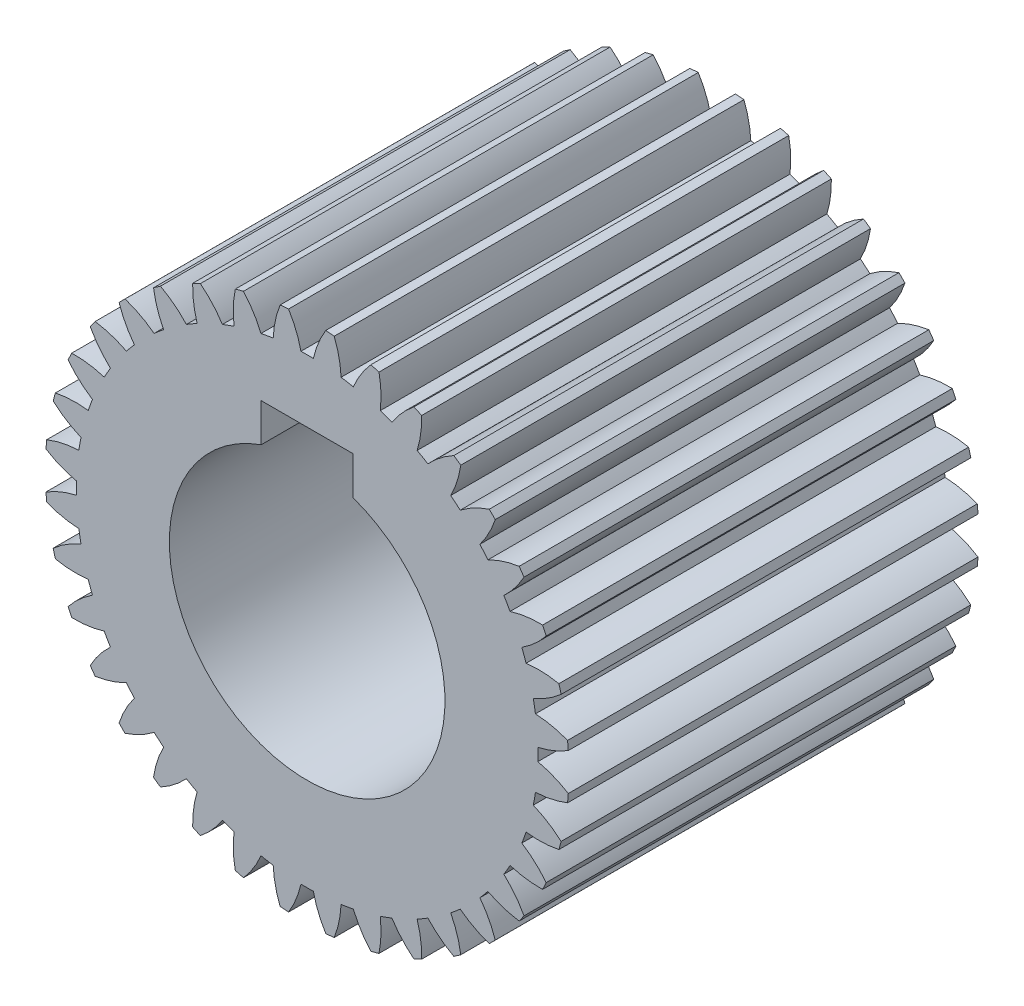
SolidWorks part; units mm, degrees
ref_plane "前视基准面" through (0, 0, 0) normal (0, 0, 1) x (1, 0, 0)
ref_plane "上视基准面" through (0, 0, 0) normal (0, 1, 0) x (1, 0, 0)
ref_plane "右视基准面" through (0, 0, 0) normal (1, 0, 0) x (0, 0, -1)
sketch "Model" plane through (0, 0, 0) normal (0, 0, 1) x (1, 0, 0)
  line L0 (-5, 18.3) -> (-5, 14.1421)
  line L1 (5, 18.3) -> (-5, 18.3)
  line L2 (5, 14.1421) -> (5, 18.3)
  arc A0 (25.1149, 0.6756) -> (28.4281, 2.0233) centre (22.7583, 11.2153) ccw
  arc A1 (28.4281, 2.0233) -> (28.3475, 2.9439) centre (0, 0) ccw
  arc A2 (28.3475, 2.9439) -> (24.8507, 3.6958) centre (24.3601, -7.093) ccw
  arc A3 (24.8507, 3.6958) -> (24.616, 5.0265) centre (0, 0) ccw
  arc A4 (24.616, 5.0265) -> (27.6449, 6.9291) centre (20.465, 14.9969) ccw
  arc A5 (27.6449, 6.9291) -> (27.4057, 7.8217) centre (0, 0) ccw
  arc A6 (27.4057, 7.8217) -> (23.8314, 7.955) centre (25.2217, -2.7552) ccw
  arc A7 (23.8314, 7.955) -> (23.3692, 9.2247) centre (0, 0) ccw
  arc A8 (23.3692, 9.2247) -> (26.0216, 11.6243) centre (17.5499, 18.3228) ccw
  arc A9 (26.0216, 11.6243) -> (25.6311, 12.4618) centre (0, 0) ccw
  arc A10 (25.6311, 12.4618) -> (22.088, 11.9724) centre (25.3169, 1.6664) ccw
  arc A11 (22.088, 11.9724) -> (21.4124, 13.1425) centre (0, 0) ccw
  arc A12 (21.4124, 13.1425) -> (23.6078, 15.9663) centre (14.1016, 21.0919) ccw
  arc A13 (23.6078, 15.9663) -> (23.0777, 16.7233) centre (0, 0) ccw
  arc A14 (23.0777, 16.7233) -> (19.6734, 15.626) centre (24.6429, 6.0373) ccw
  arc A15 (19.6734, 15.626) -> (18.8049, 16.6611) centre (0, 0) ccw
  arc A16 (18.8049, 16.6611) -> (20.4766, 19.8232) centre (10.2248, 23.2202) ccw
  arc A17 (20.4766, 19.8232) -> (19.8232, 20.4766) centre (0, 0) ccw
  arc A18 (19.8232, 20.4766) -> (16.6611, 18.8049) centre (23.2202, 10.2248) ccw
  arc A19 (16.6611, 18.8049) -> (15.626, 19.6734) centre (0, 0) ccw
  arc A20 (15.626, 19.6734) -> (16.7233, 23.0777) centre (6.0373, 24.6429) ccw
  arc A21 (16.7233, 23.0777) -> (15.9663, 23.6078) centre (0, 0) ccw
  arc A22 (15.9663, 23.6078) -> (13.1425, 21.4124) centre (21.0919, 14.1016) ccw
  arc A23 (13.1425, 21.4124) -> (11.9724, 22.088) centre (0, 0) ccw
  arc A24 (11.9724, 22.088) -> (12.4618, 25.6311) centre (1.6664, 25.3169) ccw
  arc A25 (12.4618, 25.6311) -> (11.6243, 26.0216) centre (0, 0) ccw
  arc A26 (11.6243, 26.0216) -> (9.2247, 23.3692) centre (18.3228, 17.5499) ccw
  arc A27 (9.2247, 23.3692) -> (7.955, 23.8314) centre (0, 0) ccw
  arc A28 (7.955, 23.8314) -> (7.8217, 27.4057) centre (-2.7552, 25.2217) ccw
  arc A29 (7.8217, 27.4057) -> (6.9291, 27.6449) centre (0, 0) ccw
  arc A30 (6.9291, 27.6449) -> (5.0265, 24.616) centre (14.9969, 20.465) ccw
  arc A31 (5.0265, 24.616) -> (3.6958, 24.8507) centre (0, 0) ccw
  arc A32 (3.6958, 24.8507) -> (2.9439, 28.3475) centre (-7.093, 24.3601) ccw
  arc A33 (2.9439, 28.3475) -> (2.0233, 28.4281) centre (0, 0) ccw
  arc A34 (2.0233, 28.4281) -> (0.6756, 25.1149) centre (11.2153, 22.7583) ccw
  arc A35 (0.6756, 25.1149) -> (-0.6756, 25.1149) centre (0, 0) ccw
  arc A36 (-0.6756, 25.1149) -> (-2.0233, 28.4281) centre (-11.2153, 22.7583) ccw
  arc A37 (-2.0233, 28.4281) -> (-2.9439, 28.3475) centre (0, 0) ccw
  arc A38 (-2.9439, 28.3475) -> (-3.6958, 24.8507) centre (7.093, 24.3601) ccw
  arc A39 (-3.6958, 24.8507) -> (-5.0265, 24.616) centre (0, 0) ccw
  arc A40 (-5.0265, 24.616) -> (-6.9291, 27.6449) centre (-14.9969, 20.465) ccw
  arc A41 (-6.9291, 27.6449) -> (-7.8217, 27.4057) centre (0, 0) ccw
  arc A42 (-7.8217, 27.4057) -> (-7.955, 23.8314) centre (2.7552, 25.2217) ccw
  arc A43 (-7.955, 23.8314) -> (-9.2247, 23.3692) centre (0, 0) ccw
  arc A44 (-9.2247, 23.3692) -> (-11.6243, 26.0216) centre (-18.3228, 17.5499) ccw
  arc A45 (-11.6243, 26.0216) -> (-12.4618, 25.6311) centre (0, 0) ccw
  arc A46 (-12.4618, 25.6311) -> (-11.9724, 22.088) centre (-1.6664, 25.3169) ccw
  arc A47 (-11.9724, 22.088) -> (-13.1425, 21.4124) centre (0, 0) ccw
  arc A48 (-13.1425, 21.4124) -> (-15.9663, 23.6078) centre (-21.0919, 14.1016) ccw
  arc A49 (-15.9663, 23.6078) -> (-16.7233, 23.0777) centre (0, 0) ccw
  arc A50 (-16.7233, 23.0777) -> (-15.626, 19.6734) centre (-6.0373, 24.6429) ccw
  arc A51 (-15.626, 19.6734) -> (-16.6611, 18.8049) centre (0, 0) ccw
  arc A52 (-16.6611, 18.8049) -> (-19.8232, 20.4766) centre (-23.2202, 10.2248) ccw
  arc A53 (-19.8232, 20.4766) -> (-20.4766, 19.8232) centre (0, 0) ccw
  arc A54 (-20.4766, 19.8232) -> (-18.8049, 16.6611) centre (-10.2248, 23.2202) ccw
  arc A55 (-18.8049, 16.6611) -> (-19.6734, 15.626) centre (0, 0) ccw
  arc A56 (-19.6734, 15.626) -> (-23.0777, 16.7233) centre (-24.6429, 6.0373) ccw
  arc A57 (-23.0777, 16.7233) -> (-23.6078, 15.9663) centre (0, 0) ccw
  arc A58 (-23.6078, 15.9663) -> (-21.4124, 13.1425) centre (-14.1016, 21.0919) ccw
  arc A59 (-21.4124, 13.1425) -> (-22.088, 11.9724) centre (0, 0) ccw
  arc A60 (-22.088, 11.9724) -> (-25.6311, 12.4618) centre (-25.3169, 1.6664) ccw
  arc A61 (-25.6311, 12.4618) -> (-26.0216, 11.6243) centre (0, 0) ccw
  arc A62 (-26.0216, 11.6243) -> (-23.3692, 9.2247) centre (-17.5499, 18.3228) ccw
  arc A63 (-23.3692, 9.2247) -> (-23.8314, 7.955) centre (0, 0) ccw
  arc A64 (-23.8314, 7.955) -> (-27.4057, 7.8217) centre (-25.2217, -2.7552) ccw
  arc A65 (-27.4057, 7.8217) -> (-27.6449, 6.9291) centre (0, 0) ccw
  arc A66 (-27.6449, 6.9291) -> (-24.616, 5.0265) centre (-20.465, 14.9969) ccw
  arc A67 (-24.616, 5.0265) -> (-24.8507, 3.6958) centre (0, 0) ccw
  arc A68 (-24.8507, 3.6958) -> (-28.3475, 2.9439) centre (-24.3601, -7.093) ccw
  arc A69 (-28.3475, 2.9439) -> (-28.4281, 2.0233) centre (0, 0) ccw
  arc A70 (-28.4281, 2.0233) -> (-25.1149, 0.6756) centre (-22.7583, 11.2153) ccw
  arc A71 (-25.1149, 0.6756) -> (-25.1149, -0.6756) centre (0, 0) ccw
  arc A72 (-25.1149, -0.6756) -> (-28.4281, -2.0233) centre (-22.7583, -11.2153) ccw
  arc A73 (-28.4281, -2.0233) -> (-28.3475, -2.9439) centre (0, 0) ccw
  arc A74 (-28.3475, -2.9439) -> (-24.8507, -3.6958) centre (-24.3601, 7.093) ccw
  arc A75 (-24.8507, -3.6958) -> (-24.616, -5.0265) centre (0, 0) ccw
  arc A76 (-24.616, -5.0265) -> (-27.6449, -6.9291) centre (-20.465, -14.9969) ccw
  arc A77 (-27.6449, -6.9291) -> (-27.4057, -7.8217) centre (0, 0) ccw
  arc A78 (-27.4057, -7.8217) -> (-23.8314, -7.955) centre (-25.2217, 2.7552) ccw
  arc A79 (-23.8314, -7.955) -> (-23.3692, -9.2247) centre (0, 0) ccw
  arc A80 (-23.3692, -9.2247) -> (-26.0216, -11.6243) centre (-17.5499, -18.3228) ccw
  arc A81 (-26.0216, -11.6243) -> (-25.6311, -12.4618) centre (0, 0) ccw
  arc A82 (-25.6311, -12.4618) -> (-22.088, -11.9724) centre (-25.3169, -1.6664) ccw
  arc A83 (-22.088, -11.9724) -> (-21.4124, -13.1425) centre (0, 0) ccw
  arc A84 (-21.4124, -13.1425) -> (-23.6078, -15.9663) centre (-14.1016, -21.0919) ccw
  arc A85 (-23.6078, -15.9663) -> (-23.0777, -16.7233) centre (0, 0) ccw
  arc A86 (-23.0777, -16.7233) -> (-19.6734, -15.626) centre (-24.6429, -6.0373) ccw
  arc A87 (-19.6734, -15.626) -> (-18.8049, -16.6611) centre (0, 0) ccw
  arc A88 (-18.8049, -16.6611) -> (-20.4766, -19.8232) centre (-10.2248, -23.2202) ccw
  arc A89 (-20.4766, -19.8232) -> (-19.8232, -20.4766) centre (0, 0) ccw
  arc A90 (-19.8232, -20.4766) -> (-16.6611, -18.8049) centre (-23.2202, -10.2248) ccw
  arc A91 (-16.6611, -18.8049) -> (-15.626, -19.6734) centre (0, 0) ccw
  arc A92 (-15.626, -19.6734) -> (-16.7233, -23.0777) centre (-6.0373, -24.6429) ccw
  arc A93 (-16.7233, -23.0777) -> (-15.9663, -23.6078) centre (0, 0) ccw
  arc A94 (-15.9663, -23.6078) -> (-13.1425, -21.4124) centre (-21.0919, -14.1016) ccw
  arc A95 (-13.1425, -21.4124) -> (-11.9724, -22.088) centre (0, 0) ccw
  arc A96 (-11.9724, -22.088) -> (-12.4618, -25.6311) centre (-1.6664, -25.3169) ccw
  arc A97 (-12.4618, -25.6311) -> (-11.6243, -26.0216) centre (0, 0) ccw
  arc A98 (-11.6243, -26.0216) -> (-9.2247, -23.3692) centre (-18.3228, -17.5499) ccw
  arc A99 (-9.2247, -23.3692) -> (-7.955, -23.8314) centre (0, 0) ccw
  arc A100 (-7.955, -23.8314) -> (-7.8217, -27.4057) centre (2.7552, -25.2217) ccw
  arc A101 (-7.8217, -27.4057) -> (-6.9291, -27.6449) centre (0, 0) ccw
  arc A102 (-6.9291, -27.6449) -> (-5.0265, -24.616) centre (-14.9969, -20.465) ccw
  arc A103 (-5.0265, -24.616) -> (-3.6958, -24.8507) centre (0, 0) ccw
  arc A104 (-3.6958, -24.8507) -> (-2.9439, -28.3475) centre (7.093, -24.3601) ccw
  arc A105 (-2.9439, -28.3475) -> (-2.0233, -28.4281) centre (0, 0) ccw
  arc A106 (-2.0233, -28.4281) -> (-0.6756, -25.1149) centre (-11.2153, -22.7583) ccw
  arc A107 (-0.6756, -25.1149) -> (0.6756, -25.1149) centre (0, 0) ccw
  arc A108 (0.6756, -25.1149) -> (2.0233, -28.4281) centre (11.2153, -22.7583) ccw
  arc A109 (2.0233, -28.4281) -> (2.9439, -28.3475) centre (0, 0) ccw
  arc A110 (2.9439, -28.3475) -> (3.6958, -24.8507) centre (-7.093, -24.3601) ccw
  arc A111 (3.6958, -24.8507) -> (5.0265, -24.616) centre (0, 0) ccw
  arc A112 (5.0265, -24.616) -> (6.9291, -27.6449) centre (14.9969, -20.465) ccw
  arc A113 (6.9291, -27.6449) -> (7.8217, -27.4057) centre (0, 0) ccw
  arc A114 (7.8217, -27.4057) -> (7.955, -23.8314) centre (-2.7552, -25.2217) ccw
  arc A115 (7.955, -23.8314) -> (9.2247, -23.3692) centre (0, 0) ccw
  arc A116 (9.2247, -23.3692) -> (11.6243, -26.0216) centre (18.3228, -17.5499) ccw
  arc A117 (11.6243, -26.0216) -> (12.4618, -25.6311) centre (0, 0) ccw
  arc A118 (12.4618, -25.6311) -> (11.9724, -22.088) centre (1.6664, -25.3169) ccw
  arc A119 (11.9724, -22.088) -> (13.1425, -21.4124) centre (0, 0) ccw
  arc A120 (13.1425, -21.4124) -> (15.9663, -23.6078) centre (21.0919, -14.1016) ccw
  arc A121 (15.9663, -23.6078) -> (16.7233, -23.0777) centre (0, 0) ccw
  arc A122 (16.7233, -23.0777) -> (15.626, -19.6734) centre (6.0373, -24.6429) ccw
  arc A123 (15.626, -19.6734) -> (16.6611, -18.8049) centre (0, 0) ccw
  arc A124 (16.6611, -18.8049) -> (19.8232, -20.4766) centre (23.2202, -10.2248) ccw
  arc A125 (19.8232, -20.4766) -> (20.4766, -19.8232) centre (0, 0) ccw
  arc A126 (20.4766, -19.8232) -> (18.8049, -16.6611) centre (10.2248, -23.2202) ccw
  arc A127 (18.8049, -16.6611) -> (19.6734, -15.626) centre (0, 0) ccw
  arc A128 (19.6734, -15.626) -> (23.0777, -16.7233) centre (24.6429, -6.0373) ccw
  arc A129 (23.0777, -16.7233) -> (23.6078, -15.9663) centre (0, 0) ccw
  arc A130 (23.6078, -15.9663) -> (21.4124, -13.1425) centre (14.1016, -21.0919) ccw
  arc A131 (21.4124, -13.1425) -> (22.088, -11.9724) centre (0, 0) ccw
  arc A132 (22.088, -11.9724) -> (25.6311, -12.4618) centre (25.3169, -1.6664) ccw
  arc A133 (25.6311, -12.4618) -> (26.0216, -11.6243) centre (0, 0) ccw
  arc A134 (26.0216, -11.6243) -> (23.3692, -9.2247) centre (17.5499, -18.3228) ccw
  arc A135 (23.3692, -9.2247) -> (23.8314, -7.955) centre (0, 0) ccw
  arc A136 (23.8314, -7.955) -> (27.4057, -7.8217) centre (25.2217, 2.7552) ccw
  arc A137 (27.4057, -7.8217) -> (27.6449, -6.9291) centre (0, 0) ccw
  arc A138 (27.6449, -6.9291) -> (24.616, -5.0265) centre (20.465, -14.9969) ccw
  arc A139 (24.616, -5.0265) -> (24.8507, -3.6958) centre (0, 0) ccw
  arc A140 (24.8507, -3.6958) -> (28.3475, -2.9439) centre (24.3601, 7.093) ccw
  arc A141 (28.3475, -2.9439) -> (28.4281, -2.0233) centre (0, 0) ccw
  arc A142 (28.4281, -2.0233) -> (25.1149, -0.6756) centre (22.7583, -11.2153) ccw
  arc A143 (25.1149, -0.6756) -> (25.1149, 0.6756) centre (0, 0) ccw
  arc A144 (-5, 14.1421) -> (5, 14.1421) centre (0, 0) ccw
extrude "凸台-拉伸1" add sketch "Model" along normal blind 44.6 contours A144 L2 L1 L0
